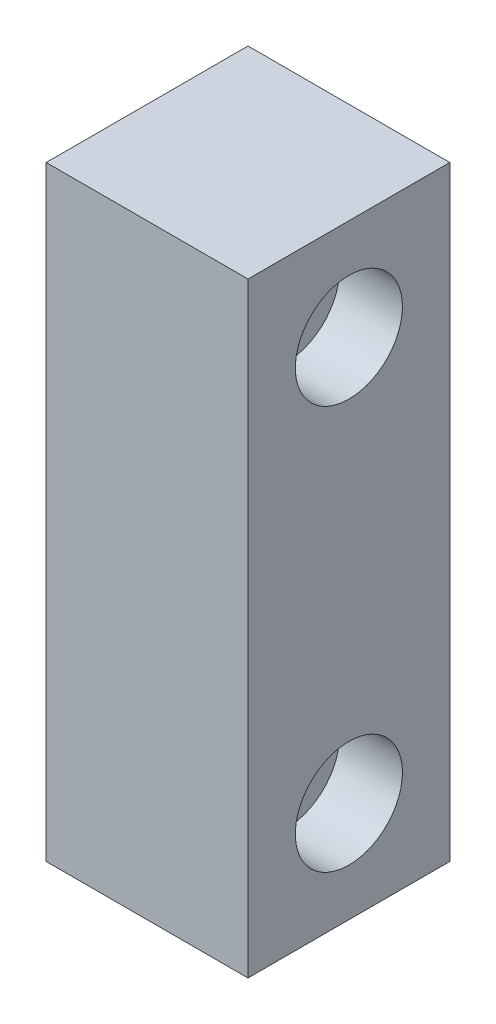
SolidWorks part; units mm, degrees
ref_plane "Front Plane" through (0, 0, 0) normal (1, 0, 0) x (0, 1, 0)
ref_plane "Top Plane" through (0, 0, 0) normal (0, 0, 1) x (0, 1, 0)
ref_plane "Right Plane" through (0, 0, 0) normal (0, 1, 0) x (-1, 0, 0)
sketch "Sketch1" plane through (0, 0, 0) normal (1, 0, 0) x (0, 1, 0)
  line L1 (0, 0) -> (76.2, 0)
  line L2 (0, 0) -> (0, 25.4)
  line L3 (0, 25.4) -> (76.2, 25.4)
  line L4 (76.2, 0) -> (76.2, 25.4)
extrude "Boss-Extrude1" add sketch "Sketch1" along normal blind 25.4
sketch "Sketch2" plane through (0, 0, 0) normal (1, 0, 0) x (0, 1, 0)
  circle A0 centre (12.7, 12.7) radius 4.3688
extrude "Cut-Extrude2" cut sketch "Sketch2" against normal blind 76.2 from offset 25.4
sketch "Sketch3" plane through (0, 0, 0) normal (1, 0, 0) x (0, 1, 0)
  circle A0 centre (12.7, 12.7) radius 6.7437
extrude "Cut-Extrude4" cut sketch "Sketch3" against normal blind 7.9248 from offset 25.4
sketch "Sketch4" plane through (0, 0, 0) normal (1, 0, 0) x (0, 1, 0)
  circle A0 centre (63.5, 12.7) radius 4.3688
extrude "Cut-Extrude6" cut sketch "Sketch4" against normal blind 76.2 from offset 25.4
sketch "Sketch5" plane through (0, 0, 0) normal (1, 0, 0) x (0, 1, 0)
  circle A0 centre (63.5, 12.7) radius 6.7437
extrude "Cut-Extrude8" cut sketch "Sketch5" against normal blind 7.9248 from offset 25.4
